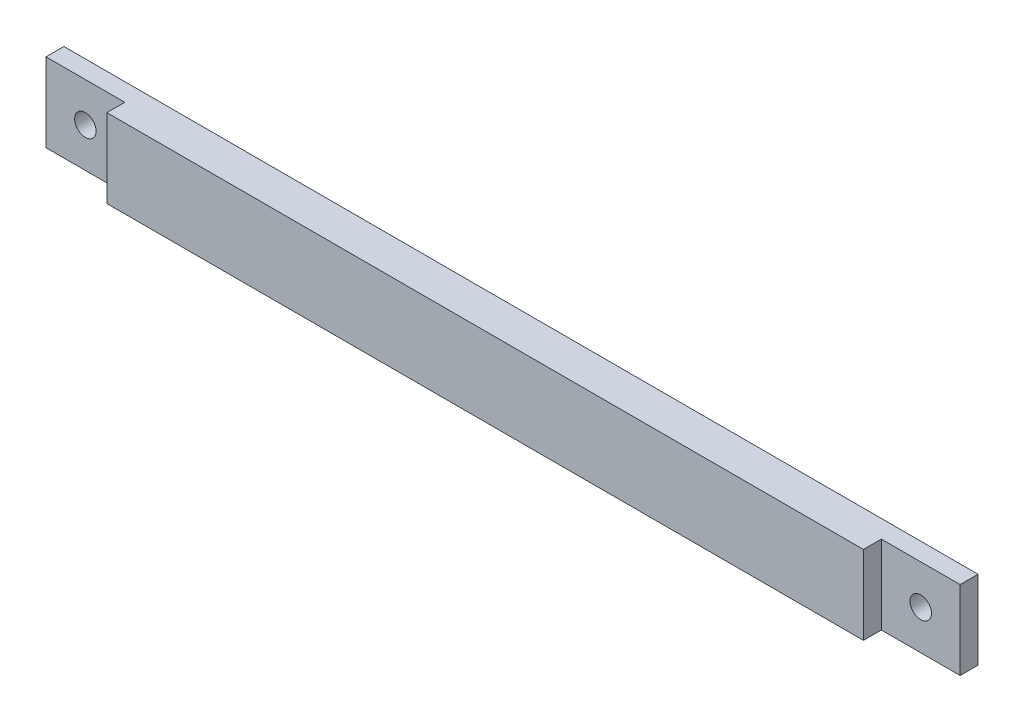
SolidWorks part; units mm, degrees
ref_plane "Plan de face" through (0, 0, 0) normal (0, 0, 1) x (1, 0, 0)
ref_plane "Plan de dessus" through (0, 0, 0) normal (0, 1, 0) x (1, 0, 0)
ref_plane "Plan de droite" through (0, 0, 0) normal (1, 0, 0) x (0, 0, -1)
sketch "Esquisse5" plane through (0, 0, 0) normal (0, 0, 1) x (1, 0, 0)
  line L1 (-86.439, 33.5176) -> (168.911, 33.5176)
  line L2 (-86.439, 33.5176) -> (-86.439, 11.5176)
  line L3 (-86.439, 11.5176) -> (168.911, 11.5176)
  line L4 (168.911, 33.5176) -> (168.911, 11.5176)
  dimension "D1" = 255.35
  dimension "D2" = 22
extrude "Boss.-Extru.1" add sketch "Esquisse5" along normal blind 10
sketch "Esquisse6" plane through (0, 0, 0) normal (0, 0, 1) x (1, 0, 0)
  line L0 (168.911, 33.5176) -> (-86.439, 33.5176) construction
  line L1 (168.911, 11.5176) -> (168.911, 33.5176) construction
  line L2 (-86.439, 33.5176) -> (-86.439, 11.5176) construction
  circle A0 centre (-75.439, 22.5176) radius 3
  circle A1 centre (157.911, 22.5176) radius 3
  dimension "D1" = 11
  dimension "D2" = 11
  dimension "D3" = 11
  dimension "D4" = 11
  dimension "D5" = 6
  dimension "D6" = 6
extrude "Enlèv. mat.-Extru.4" cut sketch "Esquisse6" along normal through all
sketch "Esquisse7" plane through (0, 0, 10) normal (0, 0, 1) x (1, 0, 0)
  line L0 (-86.439, 11.5176) -> (168.911, 11.5176) construction
  line L1 (-86.439, 33.5176) -> (-64.439, 33.5176)
  line L2 (-86.439, 33.5176) -> (-86.439, 11.5176)
  line L3 (-86.439, 11.5176) -> (-64.439, 11.5176)
  line L4 (-64.439, 33.5176) -> (-64.439, 11.5176)
  line L6 (168.911, 33.5176) -> (146.911, 33.5176)
  line L7 (168.911, 33.5176) -> (168.911, 11.5176)
  line L8 (168.911, 11.5176) -> (146.911, 11.5176)
  line L9 (146.911, 33.5176) -> (146.911, 11.5176)
  dimension "D1" = 22
  dimension "D2" = 22
extrude "Enlèv. mat.-Extru.5" cut sketch "Esquisse7" against normal blind 5
